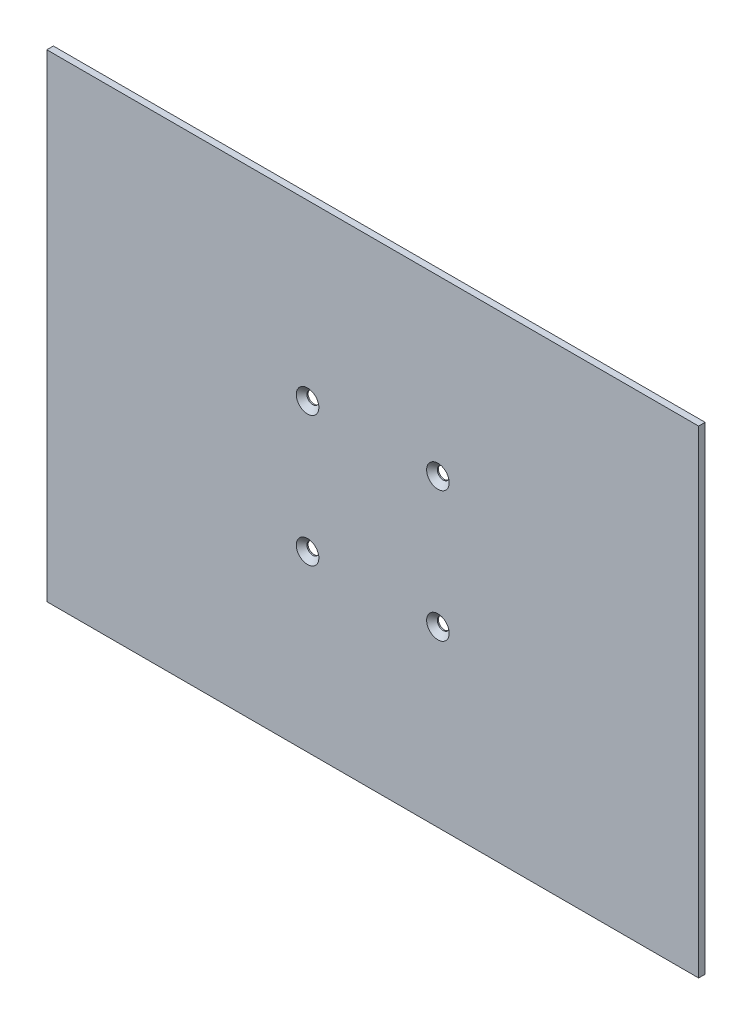
SolidWorks part; units mm, degrees
ref_plane "Front Plane" through (0, 0, 0) normal (0, 0, 1) x (1, 0, 0)
ref_plane "Top Plane" through (0, 0, 0) normal (0, 1, 0) x (1, 0, 0)
ref_plane "Right Plane" through (0, 0, 0) normal (1, 0, 0) x (0, 0, -1)
sketch "Sketch1" plane through (0, 0, 0) normal (0, 0, 1) x (1, 0, 0)
  line L1 (150, -110) -> (-150, -110)
  line L2 (150, -110) -> (150, 110)
  line L3 (150, 110) -> (-150, 110)
  line L4 (-150, -110) -> (-150, 110)
  line L5 (150, -110) -> (-150, 110) construction
  line L6 (150, 110) -> (-150, -110) construction
  point P0 (0, 0)
  dimension "D1" = 220
  dimension "D2" = 300
extrude "Boss-Extrude1" add sketch "Sketch1" along normal blind 3
hole_wizard "Fraisage pour vis à tête fraisée M51" positions "Sketch4" profile "Sketch5" countersink size "M5" standard "ISO" end condition through all
sketch "Sketch4" plane through (0, 0, 3) normal (0, 0, 1) x (1, 0, 0)
  point P0 (-30, 30)
  point P3 (30, 30)
  point P6 (-30, -30)
  point P9 (30, -30)
sketch "Sketch5" plane through (-30, 30, 3) normal (1, 0, 0) x (0, -1, 0)
  line L0 (0, 0) -> (0, 3)
  line L1 (0, 3) -> (2.75, 3)
  line L2 (2.75, 3) -> (2.75, 2.45)
  line L3 (2.75, 2.45) -> (5.2, 0)
  line L5 (5.2, 0) -> (0, 0)
  line L6 (-2.75, 2.45) -> (-5.2, 0) construction
  line L11 (0, -6.35) -> (0, 107.95) construction
  dimension "Diamètre du perçage jusqu'au prochain" = 5.5
  dimension "Profondeur du perçage jusqu'au prochain" = 3
  dimension "Diamètre du fraisage entrant" = 10.4
  dimension "Angle du fraisage entrant" = 90
